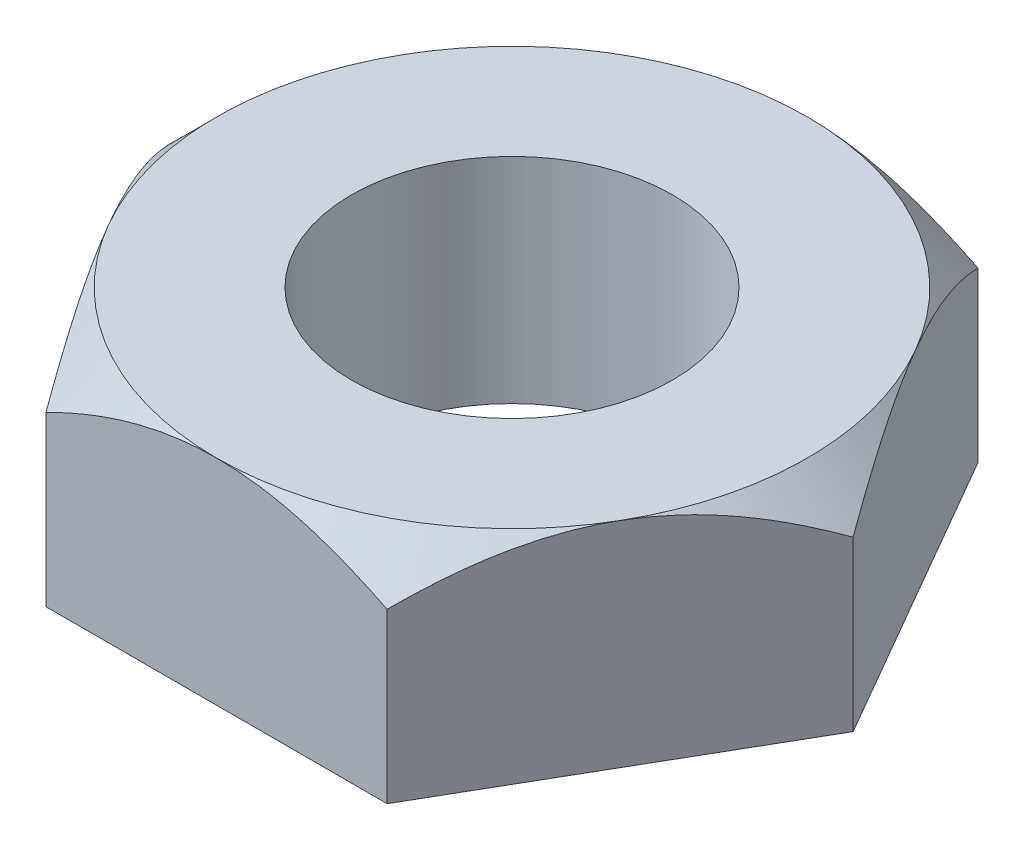
SolidWorks part; units mm, degrees
material "AISI 1045 Steel, cold drawn"
ref_plane "Front Plane" through (0, 0, 0) normal (0, 0, 1) x (1, 0, 0)
ref_plane "Top Plane" through (0, 0, 0) normal (0, 1, 0) x (1, 0, 0)
ref_plane "Right Plane" through (0, 0, 0) normal (1, 0, 0) x (0, 0, -1)
sketch "Sketch1" plane through (0, 0, 0) normal (0, 1, 0) x (1, 0, 0)
  line L1 (39.8372, 0) -> (19.9186, 34.5)
  line L2 (19.9186, 34.5) -> (-19.9186, 34.5)
  line L3 (-19.9186, 34.5) -> (-39.8372, 0)
  line L4 (-39.8372, 0) -> (-19.9186, -34.5)
  line L5 (-19.9186, -34.5) -> (19.9186, -34.5)
  line L6 (19.9186, -34.5) -> (39.8372, 0)
  circle A0 centre (0, 0) radius 34.5 construction
  circle A1 centre (0, 0) radius 18.75
  dimension "D2" = 37.5
  dimension "D1" = 69
extrude "Boss-Extrude1" add sketch "Sketch1" along normal mid plane 25
sketch "Sketch2" plane through (0, 12.5, 0) normal (0, 1, 0) x (1, 0, 0)
  circle A0 centre (0, 0) radius 34.5
  dimension "D1" = 69
extrude "Cut-Extrude1" cut sketch "Sketch2" against normal through all draft 45 flip side to cut
